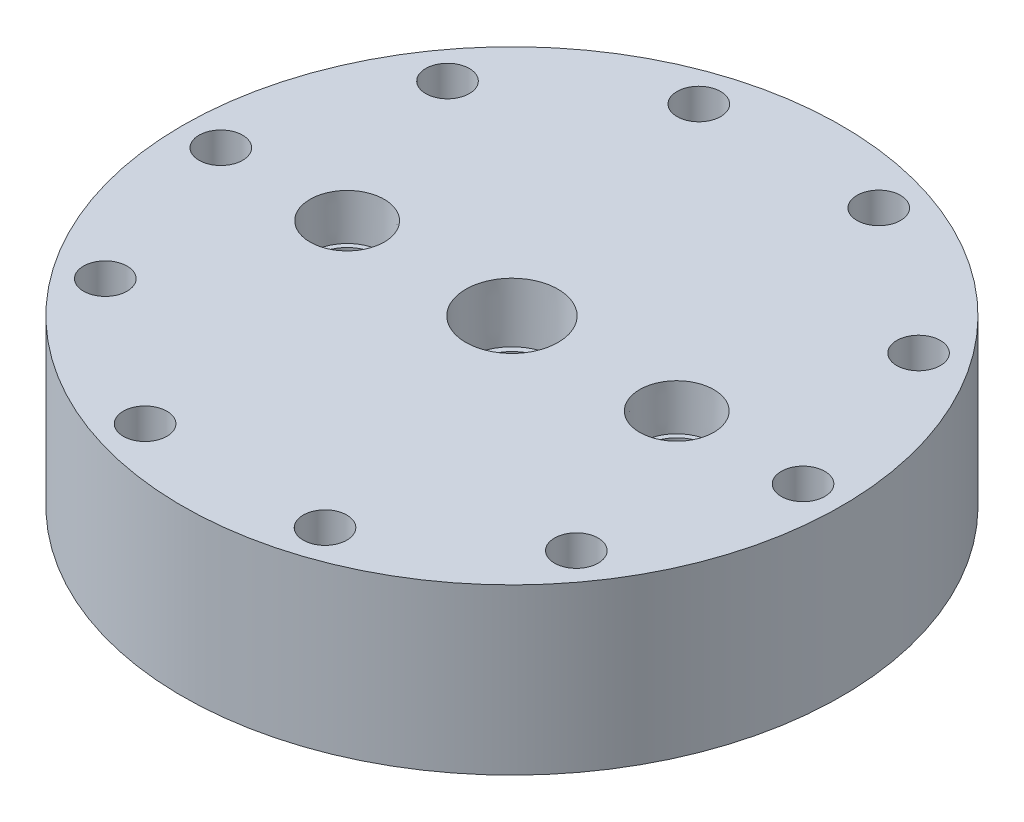
SolidWorks part; units mm, degrees
material "6061 Alloy"
ref_plane "Front Plane" through (0, 0, 0) normal (0, 0, 1) x (1, 0, 0)
ref_plane "Top Plane" through (0, 0, 0) normal (0, 1, 0) x (1, 0, 0)
ref_plane "Right Plane" through (0, 0, 0) normal (1, 0, 0) x (0, 0, -1)
sketch "Sketch1" plane through (0, 0, 0) normal (0, 0, 1) x (1, 0, 0)
  line L0 (0, 0) -> (-76.2, 0)
  line L1 (-76.2, 0) -> (-76.2, -38.1)
  line L2 (-76.2, -38.1) -> (-60.96, -38.1)
  line L3 (-60.96, -38.1) -> (-60.96, -32.258)
  line L4 (-60.96, -32.258) -> (-55.7149, -32.258)
  line L5 (0, 0) -> (0, -15.8572)
  line L8 (-28.575, -32.258) -> (-28.575, -27.178)
  line L9 (-28.575, -27.178) -> (-28.0924, -27.178)
  line L10 (-22.225, -27.178) -> (0, -15.8572)
  line L11 (-28.0924, -27.178) -> (-28.0924, -24.4856)
  line L12 (-28.0924, -24.4856) -> (-24.0284, -24.4856)
  line L13 (-24.0284, -24.4856) -> (-24.0284, -27.178)
  line L14 (-24.0284, -27.178) -> (-22.225, -27.178)
  line L15 (-55.7149, -32.258) -> (-55.7149, -29.5656)
  line L16 (-55.7149, -29.5656) -> (-51.6509, -29.5656)
  line L17 (-51.6509, -29.5656) -> (-51.6509, -32.258)
  line L18 (-51.6509, -32.258) -> (-28.575, -32.258)
  point P19 (-28.0924, -25.8318)
  point P20 (-30.5971, -32.258)
  point P21 (0, 0)
  dimension "D1" = 76.2
  dimension "D2" = 38.1
  dimension "D3" = 15.24
  dimension "D4" = 5.842
  dimension "D5" = 32.385
  dimension "D6" = 15.8572
  dimension "D7" = 6.35
  dimension "D8" = 5.08
  dimension "D9" = 4.064
  dimension "D10" = 4.064
  dimension "D11" = 2.6924
  dimension "D12" = 2.6924
  dimension "D13" = 55.7149
  dimension "D14" = 28.0924
revolve "Revolve1" add sketch "Sketch1" angle 360 about L5
hole_wizard "1/2 NPT Tapped Hole1" positions "Sketch2" profile "Sketch3" size "1/2" standard "ANSI Inch" end condition through all
sketch "Sketch2" plane through (0, 0, 0) normal (0, 1, 0) x (1, 0, 0)
  point P0 (0, 0)
sketch "Sketch3" plane through (0, 0, 0) normal (1, 0, 0) x (0, 0, 1)
  line L0 (0, 0) -> (0, 38.1)
  line L1 (0, 38.1) -> (8.9281, 38.1)
  line L2 (-10.2617, 13.462) -> (-10.6647, 0) construction
  line L3 (8.9281, 38.1) -> (8.9281, 13.462)
  line L4 (8.9281, 13.462) -> (10.2617, 13.462)
  line L5 (10.2617, 13.462) -> (10.6647, 0)
  line L7 (10.6647, 0) -> (0, 0)
  line L8 (0, -6.35) -> (0, 107.95) construction
  line L11 (-8.9281, 13.462) -> (-10.2617, 13.462) construction
  dimension "Thru Tap Drill Dia." = 17.8562
  dimension "Thru Tap Drill Depth" = 38.1
  dimension "Thread Dia." = 21.3295
  dimension "Thread Angle" = 3.43
  dimension "Thread Depth" = 13.462
hole_wizard "3/8 NPT Tapped Hole1" positions "Sketch4" profile "Sketch5" size "3/8" standard "ANSI Inch" end condition through all
sketch "Sketch4" plane through (0, 0, 0) normal (0, 1, 0) x (1, 0, 0)
  point P0 (-38.1, 0)
  point P2 (38.1, 0)
  dimension "D1" = 38.1
  dimension "D2" = 38.1
sketch "Sketch5" plane through (-38.1, 0, 0) normal (1, 0, 0) x (0, 0, 1)
  line L0 (0, 0) -> (0, 38.1)
  line L1 (0, 38.1) -> (7.1374, 38.1)
  line L2 (-8.2632, 10.414) -> (-8.575, 0) construction
  line L3 (7.1374, 38.1) -> (7.1374, 10.414)
  line L4 (7.1374, 10.414) -> (8.2632, 10.414)
  line L5 (8.2632, 10.414) -> (8.575, 0)
  line L7 (8.575, 0) -> (0, 0)
  line L8 (0, -6.35) -> (0, 107.95) construction
  line L11 (-7.1374, 10.414) -> (-8.2632, 10.414) construction
  dimension "Thru Tap Drill Dia." = 14.2748
  dimension "Thru Tap Drill Depth" = 38.1
  dimension "Thread Dia." = 17.15
  dimension "Thread Angle" = 3.43
  dimension "Thread Depth" = 10.414
hole_wizard "3/8 Clearance Hole2" positions "3DSketch3" profile "Sketch9" hole size "3/8" standard "ANSI Inch" end condition through all
sketch3d "3DSketch3"
  line L1 (0, 0, 0) -> (67.31, 0, 0) construction
  point P4 (67.31, 0, 0)
  dimension "D1" = 67.31
sketch "Sketch9" plane through (67.31, 0, 0) normal (1, 0, 0) x (0, 0, 1)
  line L0 (0, 0) -> (0, 38.1)
  line L1 (0, 38.1) -> (5.0419, 38.1)
  line L2 (5.0419, 38.1) -> (5.0419, 0)
  line L5 (5.0419, 0) -> (0, 0)
  line L11 (0, -6.35) -> (0, 107.95) construction
  dimension "Thru Hole Dia." = 10.0838
  dimension "Thru Hole Depth" = 38.1
pattern_circular "CirPattern1" count 10 over 360 about axis through (0, 0, 0) along (0, 1, 0) of "3/8 Clearance Hole2"
sketch "Sketch18" plane through (0, -32.258, 0) normal (0, -1, 0) x (1, 0, 0)
  line L0 (0, -44.45) -> (0, 44.45) construction
  circle A0 centre (0, 44.45) radius 1.27
  circle A1 centre (0, -44.45) radius 1.27
  dimension "D3" = 2.54
  dimension "D1" = 44.45
  dimension "D2" = 44.45
extrude "Cut-Extrude2" cut sketch "Sketch18" against normal blind 3.302
equation "\"D2@Sketch18\"=\"D1@Sketch18\""
